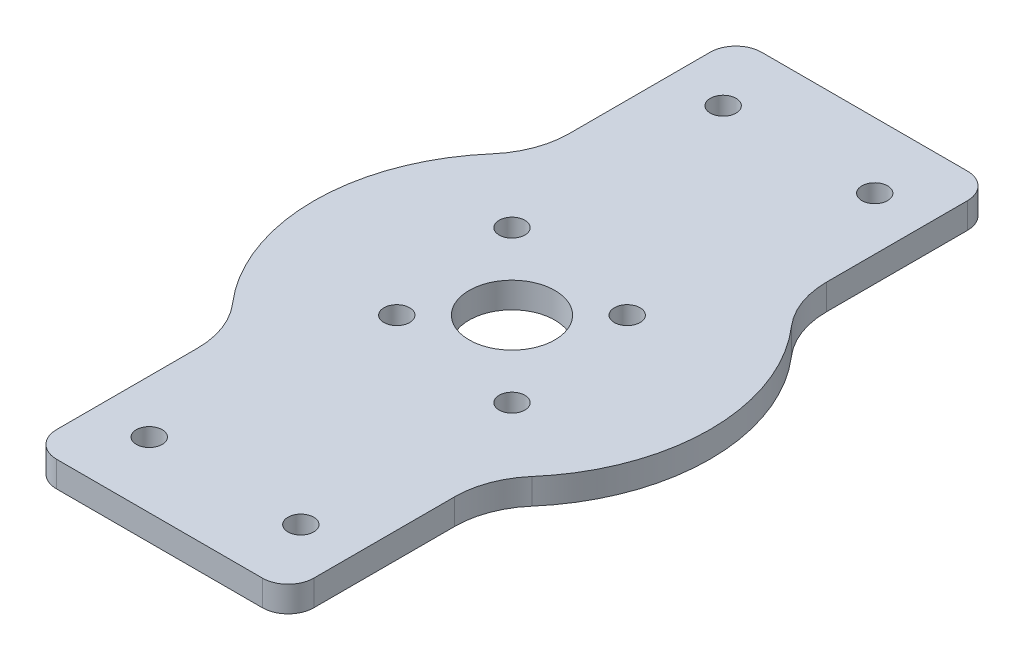
SolidWorks part; units mm, degrees
ref_plane "Front Plane" through (0, 0, 0) normal (0, 0, 1) x (1, 0, 0)
ref_plane "Top Plane" through (0, 0, 0) normal (0, 1, 0) x (1, 0, 0)
ref_plane "Right Plane" through (0, 0, 0) normal (1, 0, 0) x (0, 0, -1)
sketch "Sketch1" plane through (0, 0, 0) normal (0, 1, 0) x (1, 0, 0)
  line L0 (0, 33.4628) -> (0, -42.1291) construction
  line L1 (-39.1744, 0) -> (52.4466, 0) construction
  line L2 (-23.1, -23.1) -> (23.1, -23.1) construction
  line L3 (23.1, -23.1) -> (23.1, 23.1) construction
  line L4 (23.1, 23.1) -> (-23.1, 23.1) construction
  line L5 (-23.1, 23.1) -> (-23.1, -23.1) construction
  line L6 (-23.1, -23.1) -> (23.1, 23.1) construction
  line L7 (-23.1, 23.1) -> (23.1, -23.1) construction
  line L8 (-15, 21.6935) -> (-15, 38.108)
  line L9 (6.5, -42.6342) -> (-6.5, -42.6342) construction
  line L10 (6.5, -42.6342) -> (6.5, 42.6342) construction
  line L11 (6.5, 42.6342) -> (-6.5, 42.6342) construction
  line L12 (-6.5, -42.6342) -> (-6.5, 42.6342) construction
  line L13 (6.5, -42.6342) -> (-6.5, 42.6342) construction
  line L14 (6.5, 42.6342) -> (-6.5, -42.6342) construction
  line L15 (-15, -41.108) -> (15, -41.108) construction
  line L16 (-15, -41.108) -> (-15, 41.108) construction
  line L17 (-15, 41.108) -> (15, 41.108) construction
  line L18 (15, -41.108) -> (15, 41.108) construction
  line L19 (-15, -41.108) -> (15, 41.108) construction
  line L20 (-15, 41.108) -> (15, -41.108) construction
  line L21 (-12, 41.108) -> (12, 41.108)
  line L22 (15, 38.108) -> (15, 21.6935)
  line L23 (-15, -21.6935) -> (-15, -38.108)
  line L24 (-12, -41.108) -> (12, -41.108)
  line L25 (15, -38.108) -> (15, -21.6935)
  circle A0 centre (0, 0) radius 23.1 construction
  circle A1 centre (0, 0) radius 9.5 construction
  circle A2 centre (0, 0) radius 12.5 construction
  circle A3 centre (-8.8388, 8.8388) radius 1.5
  circle A4 centre (8.8388, -8.8388) radius 1.5
  circle A5 centre (6.7175, 6.7175) radius 1.5
  circle A6 centre (-6.7175, -6.7175) radius 1.5
  circle A7 centre (0, 0) radius 5
  arc A8 (-17.4471, 15.1396) -> (-17.4471, -15.1396) centre (0, 0) ccw
  arc A9 (17.4471, 15.1396) -> (17.4471, -15.1396) centre (0, 0) cw
  arc A10 (15, 21.6935) -> (17.4471, 15.1396) centre (25, 21.6935) ccw
  arc A11 (-17.4471, 15.1396) -> (-15, 21.6935) centre (-25, 21.6935) ccw
  arc A12 (-15, -21.6935) -> (-17.4471, -15.1396) centre (-25, -21.6935) ccw
  arc A13 (15, -21.6935) -> (17.4471, -15.1396) centre (25, -21.6935) cw
  circle A14 centre (-8.8388, 33.4628) radius 1.5
  circle A15 centre (8.8388, 33.4628) radius 1.5
  circle A16 centre (8.8388, -33.4628) radius 1.5
  circle A17 centre (-8.8388, -33.4628) radius 1.5
  arc A18 (-15, -38.108) -> (-12, -41.108) centre (-12, -38.108) ccw
  arc A19 (12, -41.108) -> (15, -38.108) centre (12, -38.108) ccw
  arc A20 (-15, 38.108) -> (-12, 41.108) centre (-12, 38.108) cw
  arc A21 (12, 41.108) -> (15, 38.108) centre (12, 38.108) cw
  point P38 (15, 17.5673)
  point P41 (-15, 17.5673)
  dimension "D1" = 46.2
  dimension "D3" = 10
  dimension "D4" = 10
  dimension "D5" = 10
  dimension "D6" = 10
  dimension "D7" = 3
  dimension "D2" = 13
extrude "Boss-Extrude1" add sketch "Sketch1" along normal blind 3
